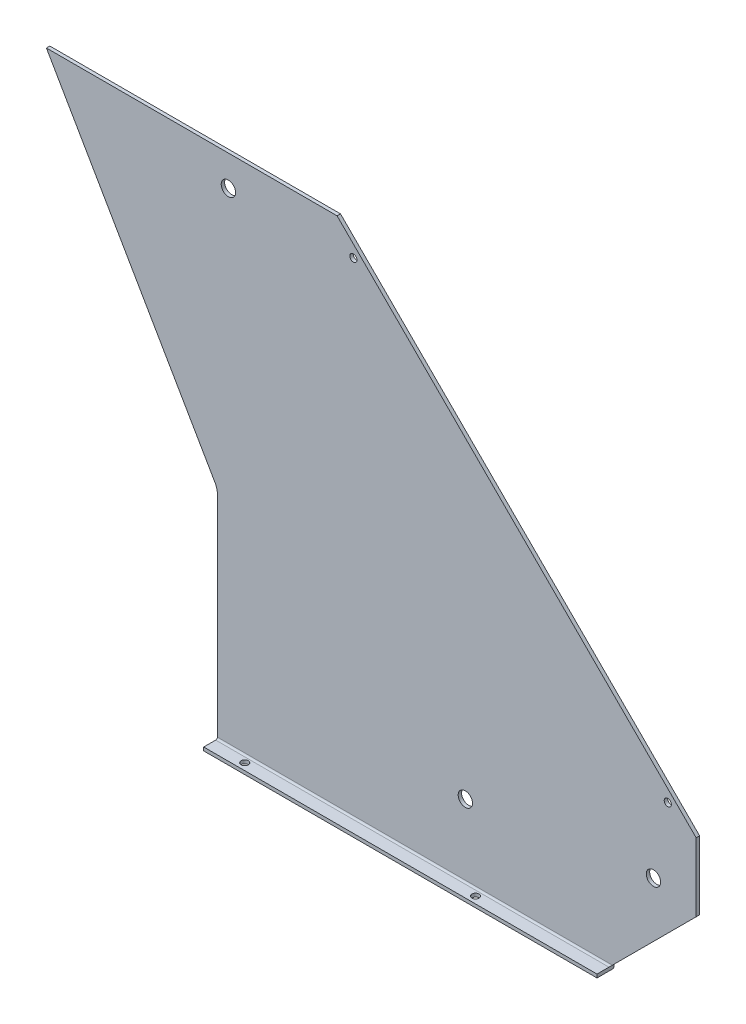
SolidWorks part; units mm, degrees
ref_plane "Plan de face" through (0, 0, 0) normal (0, 0, 1) x (1, 0, 0)
ref_plane "Plan de dessus" through (0, 0, 0) normal (0, 1, 0) x (1, 0, 0)
ref_plane "Plan de droite" through (0, 0, 0) normal (1, 0, 0) x (0, 0, -1)
sketch "Esquisse1" plane through (0, 0, 0) normal (0, 0, 1) x (1, 0, 0)
  line L0 (-70, 150) -> (140, -60)
  line L1 (-140, 150) -> (140, 150)
  line L2 (-140, -23.2051) -> (-140, -150)
  line L3 (-140, -150) -> (140, -150)
  line L4 (140, 150) -> (140, -150)
  line L5 (-140, 150) -> (140, -150) construction
  line L6 (-140, -150) -> (140, 150) construction
  line L7 (140, -100) -> (90, -150)
  line L8 (-140, 150) -> (-240, 150)
  line L9 (-240, 150) -> (-140, -23.2051)
  line L10 (-140, 150) -> (-140, -23.2051) construction
  point P0 (0, 0)
  dimension "D1" = 300
  dimension "D2" = 280
  dimension "D3" = 70
  dimension "D4" = 45
  dimension "D5" = 50
  dimension "D6" = 50
  dimension "D7" = 60
  dimension "D8" = 100
extrude "Boss.-Extru.1" add sketch "Esquisse1" along normal blind 2 contours L4 L0 L1 L2 L3
sketch "Esquisse2" plane through (0, -150, 0) normal (0, -1, 0) x (1, 0, 0)
  line L0 (90, 2) -> (90, 0) construction
  line L1 (-140, 0) -> (90, 0)
  line L2 (-140, 0) -> (-140, 10)
  line L3 (-140, 10) -> (90, 10)
  line L4 (90, 0) -> (90, 10)
  dimension "D1" = 10
extrude "Boss.-Extru.2" add sketch "Esquisse2" along normal blind 2
fillet "Congé1" radius 1 2 edges at (-25, -152, 0)
sketch "Esquisse3" plane through (0, 0, 2) normal (0, 0, 1) x (1, 0, 0)
  line L0 (-133.5641, 132.1075) -> (5, -107.8925) construction
  line L1 (5, -107.8925) -> (115, -92.8925) construction
  line L2 (-303.081, -185.3925) -> (232.511, -185.3925) construction
  line L3 (5, -107.8925) -> (5, -120.3925) construction
  line L4 (-140, -152) -> (90, -152) construction
  line L5 (0, 0) -> (79.2583, 0) construction
  line L6 (0, 0) -> (0, 50.4511) construction
  line L7 (115, -92.8925) -> (115, -105.3925) construction
  circle A0 centre (-133.5641, 132.1075) radius 4.2
  circle A1 centre (5, -107.8925) radius 4.2
  circle A2 centre (115, -92.8925) radius 4.2
  circle A3 centre (-133.5641, 132.1075) radius 12.5 construction
  circle A4 centre (5, -107.8925) radius 12.5 construction
  circle A5 centre (115, -92.8925) radius 12.5 construction
  dimension "D1" = 8.4
  dimension "D2" = 25
  dimension "D3" = 65
  dimension "D4" = 33.3925
  dimension "D5" = 60
  dimension "D6" = 5
  dimension "D7" = 110
  dimension "D8" = 80
  dimension "D9" = 240
extrude "Enlèv. mat.-Extru.1" cut sketch "Esquisse3" against normal through all
sketch "Esquisse5" plane through (0, -150, 0) normal (0, 1, 0) x (1, 0, 0)
  line L0 (79.7246, -2) -> (79.7246, -10) construction
  line L1 (90, -10) -> (-140, -10) construction
  line L2 (-140, -2) -> (91, -2) construction
  line L3 (79.7246, -6) -> (12.5895, -6) construction
  line L5 (-140, -10) -> (-140, -3) construction
  circle A0 centre (15, -6) radius 2.1
  circle A1 centre (-120, -6) radius 2.1
  point P5 (79.7246, -6)
  dimension "D3" = 4.2
  dimension "D1" = 20
  dimension "D2" = 135
extrude "Enlèv. mat.-Extru.2" cut sketch "Esquisse5" against normal through all
ref_plane "Plan1" through (0, 0, -60) normal (0, 0, 1) x (1, 0, 0)
sketch "Esquisse6" plane through (0, 0, 2) normal (0, 0, 1) x (1, 0, 0)
  line L0 (-70, 150) -> (140, -60) construction
  line L1 (-60.4594, 133.3883) -> (123.3883, -50.4594) construction
  line L2 (35, 45) -> (67.7332, 77.7332) construction
  circle A0 centre (-60.4594, 133.3883) radius 2.1
  circle A1 centre (123.3883, -50.4594) radius 2.1
  point P3 (35, 45)
  dimension "D1" = 4.2
  dimension "D2" = 5
  dimension "D3" = 130
extrude "Enlèv. mat.-Extru.3" cut sketch "Esquisse6" against normal through all contours A1 | A0
fillet "Congé2" radius 10 1 edges at (-140, -23.2051, 1)
